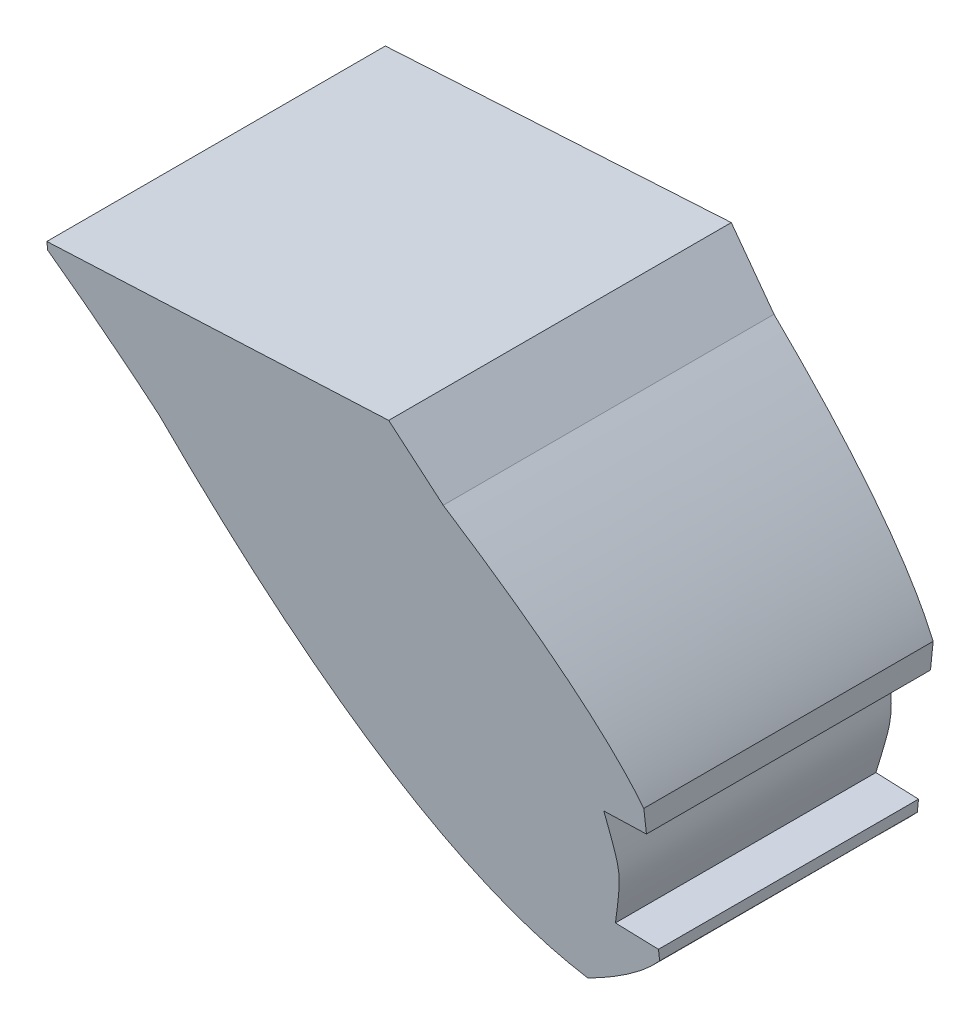
SolidWorks part; units mm, degrees
ref_plane "Alzado" through (0, 0, 0) normal (0, 0, 1) x (1, 0, 0)
ref_plane "Planta" through (0, 0, 0) normal (0, 1, 0) x (1, 0, 0)
ref_plane "Vista lateral" through (0, 0, 0) normal (1, 0, 0) x (0, 0, -1)
sketch "Croquis1" plane through (0, 0, 0) normal (0, 0, 1) x (1, 0, 0)
  line L0 (-8.9818, 12.6082) -> (-23.0359, 11.8716) construction
  line L1 (-8.9818, 12.6082) -> (-23.0359, 11.8716)
  line L2 (-8.9818, 12.6082) -> (-23.0359, 11.8716) construction
  line L4 (-8.9818, 12.6082) -> (-23.0359, 11.8716)
  line L6 (-1.3949, 1.9763) -> (0.3551, 2.2848) construction
  line L7 (-1.3949, 1.9763) -> (0.3551, 2.2848)
  line L8 (0.3551, 2.2848) -> (0.3551, 2.8423) construction
  line L9 (0.3551, 2.2848) -> (0.3551, 3.0015)
  line L10 (0.3551, -2.2848) -> (-1.3949, -2.2237) construction
  line L11 (0.3551, -2.2848) -> (-1.3949, -2.2237)
  line L12 (0.3551, 2.2848) -> (0.3551, -2.2848) construction
  line L13 (0.3551, -2.2848) -> (0.3551, -2.7233)
  line L14 (-8.9818, 12.6082) -> (-6.9949, 10.4774)
  line L15 (-23.0359, 11.5401) -> (-23.0359, 11.8716) construction
  line L16 (-23.0359, 11.5401) -> (-23.0359, 11.8716)
  arc A0 (-18.9452, 7.5409) -> (-23.0359, 11.5401) centre (-69.8841, -40.4718) ccw construction
  arc A1 (-18.9452, 7.5409) -> (-23.0359, 11.5401) centre (-69.8841, -40.4718) ccw
  spline S1 degree 2 poles (-828.7061, 3922.2202) (545.889, -3962.7836) (-262.0834, 3982.5902) knots 0.462185 0.462185 0.462185 0.537731 0.537731 0.537731 weights 1 1 1 only from (-18.9452, 7.5409) to (-2.8466, -5.0591) construction
  spline S2 degree 2 poles (-18.9452, 7.5409) (-10.215, -3.6976) (-2.8466, -5.0591) knots 0.497667 0.497667 0.497667 0.499554 0.499554 0.499554 weights 1 1 1
  spline S3 degree 2 poles (-3804.8689, 1232.5771) (3762.9122, -1369.6643) (-3716.5752, 1504.852) knots 0.462212 0.462212 0.462212 0.537836 0.537836 0.537836 weights 1 1 1 only from (0.3551, 3.0015) to (-6.9949, 10.4774) construction
  spline S4 degree 2 poles (0.3551, 3.0015) (-1.4487, 6.0584) (-6.9949, 10.4774) knots 0.500821 0.500821 0.500821 0.502013 0.502013 0.502013 weights 1 1 1
  spline S5 degree 2 poles (-1.3949, -2.2237) (-0.9075, -0.1237) (-1.3949, 1.9763) knots 0 0 0 1 1 1 weights 1 3.231801 1 construction
  spline S6 degree 2 poles (-1.3949, -2.2237) (-0.9075, -0.1237) (-1.3949, 1.9763) knots 0 0 0 1 1 1 weights 1 3.231801 1
  spline S7 degree 2 poles (-3997.263, 185.0077) (3984.2333, -348.7483) (-3965.0625, 511.2595) knots 0.462205 0.462205 0.462205 0.537778 0.537778 0.537778 weights 1 1 1 only from (-2.8466, -5.0591) to (0.3551, -2.7233) construction
  spline S8 degree 2 poles (-2.8466, -5.0591) (-0.7424, -3.9352) (0.3551, -2.7233) knots 0.498812 0.498812 0.498812 0.499413 0.499413 0.499413 weights 1 1 1
extrude "Saliente-Extruir1" add sketch "Croquis1" along normal mid plane 14 contours S2 S8 L13 L11 S6 L7 L9 S4 L14 L1 L16 A1
sketch "Croquis3" plane through (0, 0, 0) normal (0, 0, 1) x (1, 0, 0)
  line L0 (-6.742, 0) -> (0, 0) construction
  line L1 (-1.8181, 2) -> (-1.7771, 2.0103) construction
  line L3 (-1.8181, 2) -> (-0.1689, 2.4155) construction
  line L4 (-1.8181, 2) -> (0.3551, 3.0015)
  line L5 (0.3551, 3.0015) -> (0.3551, 0)
  line L6 (-1.9135, -2.1825) -> (0.3551, -2.2848)
  line L7 (0.3551, -2.2848) -> (0.3551, 0)
  parabola Q0 (-1.9135, -2.1825) -> (-1.8181, 2) focus (-3.3181, 0) apex (-1.3181, 0)
  dimension "D1" = 2
  dimension "D2" = 2
extrude "Cortar-Extruir1" [suppressed] cut sketch "Croquis3" against normal through all both and the other way through all
sketch "Croquis4" plane through (0, 0, 0) normal (0, 0, 1) x (1, 0, 0)
  line L0 (-1.3949, 1.9763) -> (0.3551, 2.2848) construction
  line L1 (-1.3949, 1.9763) -> (0.3551, 2.2848)
  line L2 (0.3551, 2.2848) -> (0.3551, 3.0015) construction
  line L3 (0.3551, 2.0374) -> (0.3551, 2.2848)
  line L4 (-1.3949, 1.9763) -> (0.3551, 2.0374)
  line L5 (0, 0) -> (-3.4665, 0) construction
  dimension "D1" = 2
extrude "Saliente-Extruir2" add sketch "Croquis4" along normal through all and the other way through all
sketch "Croquis7" plane through (0, 0, 0) normal (0, 0, 1) x (1, 0, 0)
  line L0 (0, 0) -> (-15.3945, 3.3171) construction
  line L1 (-17.3963, 18.9371) -> (-15.3945, 3.3171) construction
  line L2 (-15.3945, 3.3171) -> (-9.9316, -2.6296) construction
  line L3 (-15.3945, 3.3171) -> (-10.2385, 8.0535) construction
  line L4 (-17.3963, 18.9371) -> (-16.5429, 12.2783) construction
  line L5 (0, 0) -> (-1.3461, -2.2254) construction
  line L6 (-69.8841, 29.5282) -> (-81.9382, 42.5765) construction
  line L7 (-69.8841, 29.5282) -> (-20.9497, 29.5282) construction
  line L8 (-17.8101, 13.1658) -> (-25.5429, 13.1658)
  line L9 (-18.2059, 7.0951) -> (-21.9246, 11.9299) construction
  line L10 (0.3551, -2.5) -> (-2.4497, -2.0473)
  line L11 (-1.3461, -2.2254) -> (-2.0075, -3.6222) construction
  line L12 (-1.3461, -2.2254) -> (-1.4547, -2.8987) construction
  line L13 (-1.3461, -2.2254) -> (-1.2286, -1.4976) construction
  line L14 (0.3551, -2.2848) -> (0.3551, -2.7233) construction
  line L15 (0.3551, -2.2848) -> (-1.3949, -2.2237) construction
  line L16 (-2.0075, -3.6222) -> (-3.0629, -5.8512) construction
  line L17 (-2.6331, -4.9434) -> (-3.7044, -5.5324) construction
  line L18 (-2.6331, -4.9434) -> (-3.2248, -3.867) construction
  line L19 (-2.6331, -4.9434) -> (-2.2174, -6.1341) construction
  line L20 (-4.0838, -4.7637) -> (-1.6363, -5.0668) construction
  line L21 (-4.0838, -4.7637) -> (-0.036, -5.9454) construction
  line L22 (-4.0838, -4.7637) -> (-3.7621, -3.6616) construction
  line L23 (-4.0838, -4.7637) -> (-6.31, -3.7023) construction
  line L24 (-6.31, -3.7023) -> (-8.69, -2.5677) construction
  line L25 (-8.69, -2.5677) -> (-6.8421, -3.7725) construction
  line L26 (-8.69, -2.5677) -> (-7.9481, -1.4297) construction
  line L27 (-10.6884, -0.8477) -> (-8.69, -2.5677) construction
  line L28 (-10.6884, -0.8477) -> (-14.8546, 2.738) construction
  line L29 (-14.8546, 2.738) -> (-14.5337, 2.3989) construction
  line L30 (-14.8546, 2.738) -> (-14.6199, 2.9602) construction
  line L31 (-18.2059, 7.0951) -> (-14.8546, 2.738) construction
  line L32 (-8.9818, 12.6082) -> (-23.0359, 11.8716) construction
  line L33 (-8.9818, 12.6082) -> (-23.0359, 11.8716)
  line L34 (-21.9246, 11.9299) -> (-21.9826, 13.0367) construction
  line L35 (-21.9246, 11.9299) -> (-23.4156, 13.0367) construction
  arc A0 (-18.9452, 7.5409) -> (-23.0359, 11.5401) centre (-69.8841, -40.4718) ccw construction
  spline S0 degree 2 poles (-654.4568, 2937.5195) (409.3679, -2972.9237) (-163.476, 2987.5518) knots 0.467242 0.467242 0.467242 0.532662 0.532662 0.532662 weights 1 1 1 only from (-18.9452, 7.5409) to (-2.8466, -5.0591) construction
  spline S1 degree 2 poles (-18.6263, 7.1332) (-10.0803, -3.7225) (-2.8466, -5.0591) knots 0.497702 0.497702 0.497702 0.499554 0.499554 0.499554 weights 1 1 1 construction
  spline S3 degree 2 poles (-2999.4042, 119.7504) (2988.2948, -261.6206) (-2971.0465, 402.239) knots 0.467267 0.467267 0.467267 0.532713 0.532713 0.532713 weights 1 1 1 only from (-2.8466, -5.0591) to (0.3551, -2.7233) construction
  spline S4 degree 2 poles (-2.8466, -5.0591) (-2.7385, -5.0013) (-2.6331, -4.9434) knots 0.498812 0.498812 0.498812 0.498843 0.498843 0.498843 weights 1 1 1
  dimension "D1" = 2.5
  dimension "D2" = 23
  dimension "D3" = 16.17
  dimension "D4" = 54.138
  dimension "D5" = 34.566
  dimension "D6" = 50.413
sketch "Croquis6" plane through (0, 0, 0) normal (1, 0, 0) x (0, 0, -1)
  line L0 (7, 12.6082) -> (7, 10.4774) construction
  line L1 (7, 12.6082) -> (7, -5.0591)
  line L2 (-7, 12.6082) -> (-7, 10.4774) construction
  line L3 (-7, 12.6082) -> (-7, -5.0591)
  line L4 (-7, -5.0591) -> (7, -5.0591) construction
  line L5 (-7, -5.0591) -> (-5, -5.0591)
  line L6 (7, 12.6082) -> (5, -5.0591)
  line L7 (-7, 12.6082) -> (-5, -5.0591)
  line L8 (5, -5.0591) -> (7, -5.0591)
  dimension "D1" = 2
  dimension "D2" = 2
extrude "Cortar-Extruir2" cut sketch "Croquis6" against normal through all and the other way through all
